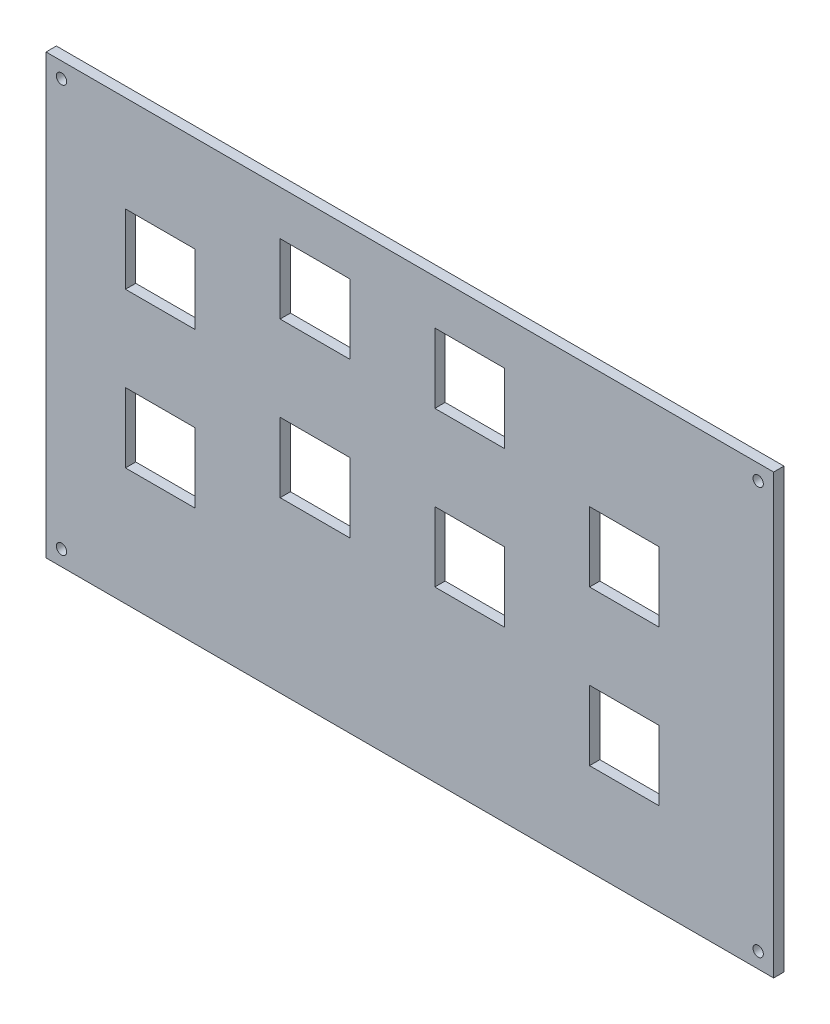
SolidWorks part; units mm, degrees
ref_plane "Front Plane" through (0, 0, 0) normal (0, 0, 1) x (1, 0, 0)
ref_plane "Top Plane" through (0, 0, 0) normal (0, 1, 0) x (1, 0, 0)
ref_plane "Right Plane" through (0, 0, 0) normal (1, 0, 0) x (0, 0, -1)
sketch "Sketch1" plane through (0, 0, 0) normal (0, 0, 1) x (-1, 0, 0)
  line L0 (85.25, -38.25) -> (98.75, -38.25)
  line L1 (98.75, -8.25) -> (85.25, 5.25) construction
  line L2 (85.25, -8.25) -> (98.75, -8.25)
  line L3 (85.25, -8.25) -> (85.25, 5.25)
  line L4 (85.25, 5.25) -> (98.75, 5.25)
  line L5 (98.75, -8.25) -> (98.75, 5.25)
  line L6 (98.75, 5.25) -> (85.25, -8.25) construction
  line L7 (85.25, -38.25) -> (85.25, -24.75)
  line L8 (85.25, -24.75) -> (98.75, -24.75)
  line L9 (98.75, -38.25) -> (98.75, -24.75)
  line L18 (55.25, -48.25) -> (68.75, -48.25)
  line L19 (55.25, -18.25) -> (68.75, -18.25)
  line L20 (55.25, -18.25) -> (55.25, -4.75)
  line L21 (55.25, -4.75) -> (68.75, -4.75)
  line L22 (68.75, -18.25) -> (68.75, -4.75)
  line L23 (55.25, -48.25) -> (55.25, -34.75)
  line L24 (55.25, -34.75) -> (68.75, -34.75)
  line L25 (68.75, -48.25) -> (68.75, -34.75)
  line L26 (25.25, -48.25) -> (38.75, -48.25)
  line L27 (25.25, -18.25) -> (38.75, -18.25)
  line L28 (25.25, -18.25) -> (25.25, -4.75)
  line L29 (25.25, -4.75) -> (38.75, -4.75)
  line L30 (38.75, -18.25) -> (38.75, -4.75)
  line L31 (25.25, -48.25) -> (25.25, -34.75)
  line L32 (25.25, -34.75) -> (38.75, -34.75)
  line L33 (38.75, -48.25) -> (38.75, -34.75)
  line L34 (-4.75, -33.25) -> (8.75, -33.25)
  line L35 (-4.75, -3.25) -> (8.75, -3.25)
  line L36 (-4.75, -3.25) -> (-4.75, 10.25)
  line L37 (-4.75, 10.25) -> (8.75, 10.25)
  line L38 (8.75, -3.25) -> (8.75, 10.25)
  line L39 (-4.75, -33.25) -> (-4.75, -19.75)
  line L40 (-4.75, -19.75) -> (8.75, -19.75)
  line L41 (8.75, -33.25) -> (8.75, -19.75)
  line L42 (98.75, -24.75) -> (85.25, -38.25) construction
  line L43 (98.75, -38.25) -> (85.25, -24.75) construction
  line L44 (68.75, -4.75) -> (55.25, -18.25) construction
  line L45 (68.75, -18.25) -> (55.25, -4.75) construction
  line L46 (68.75, -34.75) -> (55.25, -48.25) construction
  line L47 (55.25, -34.75) -> (68.75, -48.25) construction
  line L48 (38.75, -34.75) -> (25.25, -48.25) construction
  line L49 (38.75, -48.25) -> (25.25, -34.75) construction
  line L50 (125, 61.5) -> (-125, 61.5)
  line L51 (-125, 61.5) -> (-125, -61.5)
  line L52 (-125, -61.5) -> (125, -61.5)
  line L53 (125, -61.5) -> (125, 61.5)
  line L54 (38.75, -4.75) -> (25.25, -18.25) construction
  line L55 (25.25, -4.75) -> (38.75, -18.25) construction
  line L56 (8.75, -19.75) -> (-4.75, -33.25) construction
  line L57 (-4.75, -19.75) -> (8.75, -33.25) construction
  line L58 (8.75, 10.25) -> (-4.75, -3.25) construction
  line L59 (-4.75, 10.25) -> (8.75, -3.25) construction
  point P0 (92, -1.5)
  point P1 (92, -31.5)
  point P6 (62, -11.5)
  point P7 (62, -41.5)
  point P10 (32, -41.5)
  point P16 (32, -11.5)
  point P18 (2, -26.5)
  point P19 (2, 3.5)
  dimension "D1" = 13.5
  dimension "D2" = 13.5
  dimension "D5" = 13.5
  dimension "D6" = 13.5
  dimension "D9" = 13.5
  dimension "D10" = 13.5
  dimension "D11" = 13.5
  dimension "D12" = 13.5
  dimension "D13" = 13.5
  dimension "D14" = 13.5
  dimension "D15" = 13.5
  dimension "D16" = 13.5
  dimension "D17" = 13.5
  dimension "D18" = 13.5
  dimension "D19" = 13.5
  dimension "D20" = 13.5
extrude "Boss-Extrude1" add sketch "Sketch1" along normal blind 2
sketch "Sketch2" plane through (0, 0, 0) normal (0, 0, -1) x (-1, 0, 0)
  line L0 (2, 26.5) -> (8.75, 26.5) construction
  line L1 (2, 26.5) -> (-4.75, 26.5) construction
  line L2 (-4.75, 19.75) -> (-4.75, 33.25) construction
  line L3 (2, 33.25) -> (2, 19.75) construction
  line L4 (-4.75, 33.25) -> (8.75, 33.25) construction
  line L5 (8.75, 19.75) -> (-4.75, 19.75) construction
  line L6 (8.75, 33.25) -> (8.75, 19.75) construction
sketch "Sketch3" plane through (0, 0, 2) normal (0, 0, 1) x (1, 0, 0)
  line L1 (-114.1446, 56.9077) -> (26.9507, 56.9077)
  line L2 (-114.1446, 56.9077) -> (-114.1446, -28.0625)
  line L3 (-114.1446, -28.0625) -> (26.9507, -28.0625)
  line L4 (26.9507, 56.9077) -> (26.9507, -28.0625)
  line L8 (-125, 61.5) -> (-125, -61.5)
  line L9 (-125, -61.5) -> (125, -61.5)
  line L10 (125, -61.5) -> (125, 61.5)
  line L11 (125, 61.5) -> (-125, 61.5)
  line L12 (-125, 61.5) -> (-125, -61.5)
  line L13 (-125, -61.5) -> (125, -61.5)
  line L14 (125, -61.5) -> (125, 61.5)
  line L15 (125, 61.5) -> (-125, 61.5)
  dimension "D1" = 0
extrude "Cut-Extrude2" cut sketch "Sketch3" against normal blind 62 contours L12 L13 L14 L15 | L2 L1 L4 L3
sketch "Sketch4" plane through (0, 0, 2) normal (0, 0, 1) x (1, 0, 0)
  line L0 (26.9507, 56.9077) -> (26.9507, -28.0625) construction
  line L1 (-114.1446, -28.0625) -> (26.9507, -28.0625) construction
  line L2 (-114.1446, 56.9077) -> (26.9507, 56.9077) construction
  line L3 (-114.1446, 56.9077) -> (-114.1446, -28.0625) construction
  circle A0 centre (23.9507, -25.0625) radius 1
  circle A1 centre (23.9507, 53.9077) radius 1
  circle A2 centre (-111.1446, 53.9077) radius 1
  circle A3 centre (-111.1446, -25.0625) radius 1
  dimension "D2" = 2
  dimension "D3" = 3
  dimension "D4" = 3
  dimension "D6" = 2
  dimension "D7" = 3
  dimension "D8" = 3
  dimension "D9" = 2
  dimension "D11" = 3
  dimension "D12" = 2
  dimension "D1" = 3
  dimension "D5" = 3
  dimension "D10" = 3
extrude "Cut-Extrude3" cut sketch "Sketch4" against normal blind 62
